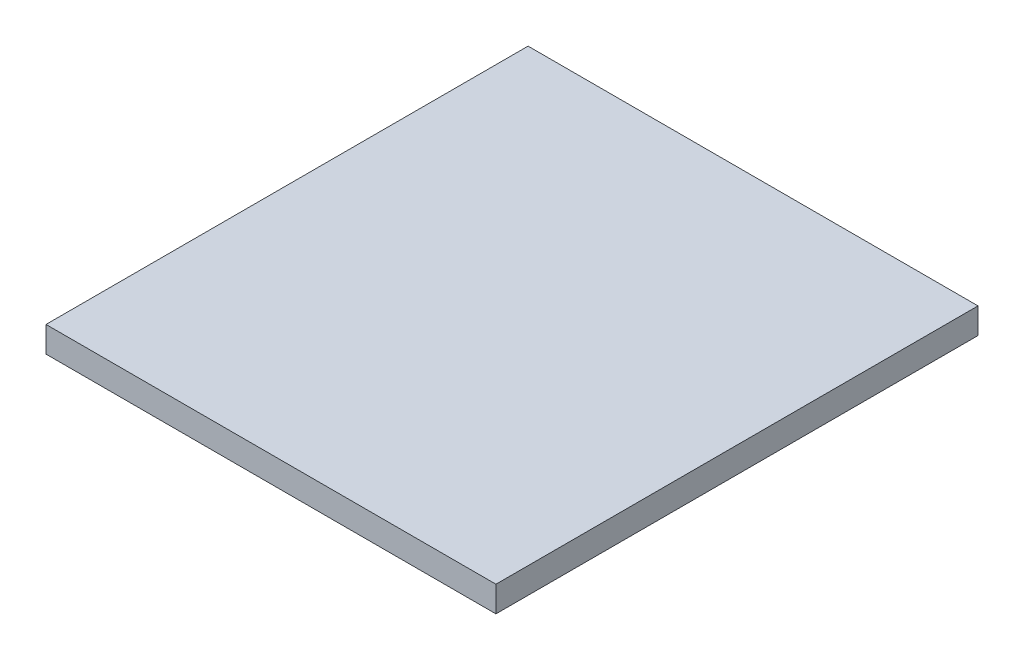
SolidWorks part; units mm, degrees
ref_plane "Front Plane" through (0, 0, 0) normal (0, 0, 1) x (1, 0, 0)
ref_plane "Top Plane" through (0, 0, 0) normal (0, 1, 0) x (1, 0, 0)
ref_plane "Right Plane" through (0, 0, 0) normal (1, 0, 0) x (0, 0, -1)
sketch "Sketch1" plane through (0, 0, 0) normal (0, 1, 0) x (1, 0, 0)
  line L1 (-17.5, -18.75) -> (17.5, -18.75)
  line L2 (-17.5, -18.75) -> (-17.5, 18.75)
  line L5 (-17.5, 18.75) -> (17.5, 18.75)
  line L6 (17.5, -18.75) -> (17.5, 18.75)
  line L7 (-17.5, -18.75) -> (17.5, 18.75) construction
  line L8 (-17.5, 18.75) -> (17.5, -18.75) construction
  point P0 (0, 0)
  dimension "D1" = 37.5
  dimension "D2" = 35
extrude "Boss-Extrude1" add sketch "Sketch1" along normal blind 2
